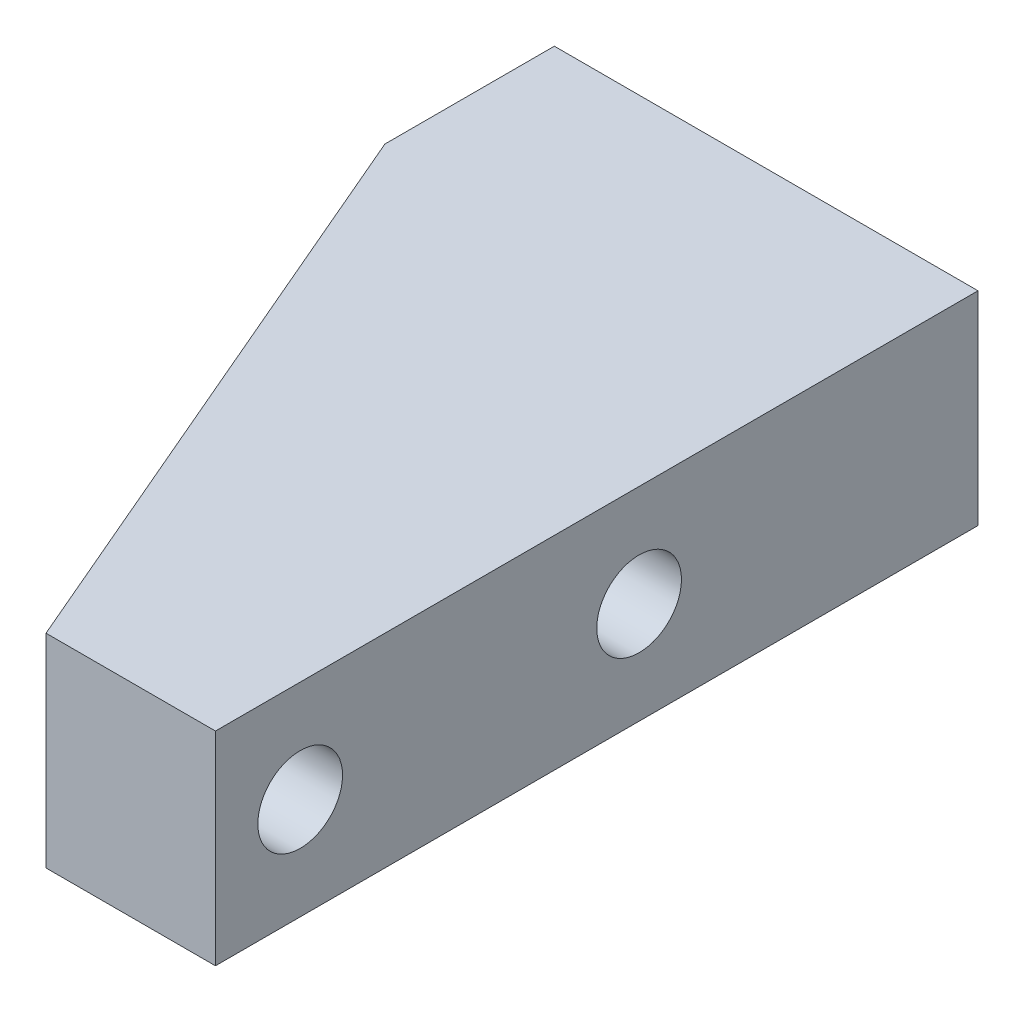
SolidWorks part; units mm, degrees
material "6061"
ref_plane "前视" through (0, 0, 0) normal (0, 0, 1) x (1, 0, 0)
ref_plane "上视" through (0, 0, 0) normal (0, 1, 0) x (1, 0, 0)
ref_plane "右视" through (0, 0, 0) normal (1, 0, 0) x (0, 0, -1)
sketch "草图1" plane through (0, 0, 0) normal (0, 1, 0) x (1, 0, 0)
  line L0 (0, 0) -> (25, 0)
  line L1 (25, 0) -> (25, -45)
  line L2 (25, -45) -> (15, -45)
  line L3 (15, -45) -> (0, -10)
  line L4 (0, -10) -> (0, 0)
  dimension "D1" = 25
  dimension "D2" = 45
  dimension "D3" = 10
extrude "凸台-拉伸1" add sketch "草图1" along normal mid plane 12
hole_wizard "M6 螺纹孔2" positions "草图3" profile "草图2" tap size "M6" standard "Gb"
sketch "草图3" plane through (25, 0, 0) normal (1, 0, 0) x (0, 0, -1)
  line L0 (0, 0) -> (-45, 0) construction
  line L1 (-45, 6) -> (-45, -6) construction
  line L2 (-30, 6) -> (-30, 2.1586) construction
  line L4 (0, 6) -> (0, -6) construction
  point P0 (-20, 0)
  point P16 (-40, 0)
  dimension "D1" = 20
  dimension "D2" = 20
sketch "草图2" plane through (25, 0, 20) normal (0, 1, 0) x (0, 0, -1)
  line L0 (0, 0) -> (0, 16.5022)
  line L1 (0, 16.5022) -> (2.5, 15)
  line L2 (2.5, 15) -> (2.5, 0)
  line L5 (2.5, 0) -> (0, 0)
  line L10 (0, 16.5022) -> (-2.5, 15) construction
  line L11 (0, -6.35) -> (0, 107.95) construction
  dimension "螺纹孔钻头直径" = 5
  dimension "螺纹孔钻头深度" = 15
  dimension "导头角度" = 118
cosmetic thread "孔螺蚊线1" parameters "D1"=12, "D2"=6
cosmetic thread "孔螺蚊线2" parameters "D1"=12, "D2"=6
hole_wizard "M6 螺纹孔1" positions "草图5" profile "草图4" tap size "M6" standard "Gb"
sketch "草图5" plane through (0, 0, 0) normal (0, 0, -1) x (-1, 0, 0)
  line L0 (-12.5, 6) -> (-12.5, -3.0633) construction
  line L1 (-25, 6) -> (0, 6) construction
  line L3 (-25, 6) -> (-25, -6) construction
  line L4 (-11.7857, 0) -> (-25, 0) construction
  point P12 (-6, 0)
  dimension "D1" = 19
sketch "草图4" plane through (6, 0, 0) normal (1, 0, 0) x (0, 1, 0)
  line L0 (0, 0) -> (0, 16.5022)
  line L1 (0, 16.5022) -> (2.5, 15)
  line L2 (2.5, 15) -> (2.5, 0)
  line L5 (2.5, 0) -> (0, 0)
  line L10 (0, 16.5022) -> (-2.5, 15) construction
  line L11 (0, -6.35) -> (0, 107.95) construction
  dimension "螺纹孔钻头直径" = 5
  dimension "螺纹孔钻头深度" = 15
  dimension "导头角度" = 118
cosmetic thread "孔螺蚊线3" parameters "D1"=12, "D2"=6
